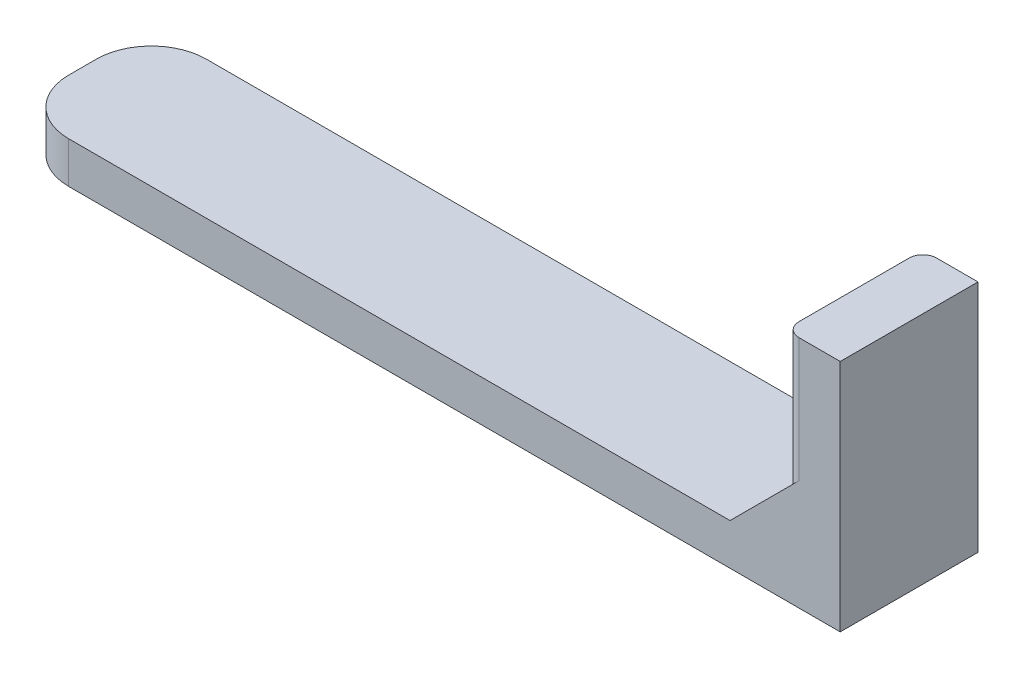
SolidWorks part; units mm, degrees
ref_plane "Plano frontal" through (0, 0, 0) normal (0, 0, 1) x (1, 0, 0)
ref_plane "Plano superior" through (0, 0, 0) normal (0, 1, 0) x (1, 0, 0)
ref_plane "Plano direito" through (0, 0, 0) normal (1, 0, 0) x (0, 0, -1)
sketch "Esboço1" plane through (0, 0, 0) normal (0, 1, 0) x (1, 0, 0)
  line L1 (-15, -2.5) -> (15, -2.5)
  line L2 (-15, -2.5) -> (-15, 2.5)
  line L3 (-15, 2.5) -> (15, 2.5)
  line L4 (15, -2.5) -> (15, 2.5)
  line L5 (-15, -2.5) -> (15, 2.5) construction
  line L6 (-15, 2.5) -> (15, -2.5) construction
  point P0 (0, 0)
  dimension "D1" = 30
  dimension "D2" = 5
extrude "Ressalto-extrusão1" add sketch "Esboço1" along normal blind 1.5
sketch "Esboço2" plane through (0, 1.5, 0) normal (0, 1, 0) x (1, 0, 0)
  line L0 (15, 2.5) -> (-15, 2.5) construction
  line L1 (15, -2.5) -> (13, -2.5)
  line L2 (15, -2.5) -> (15, 2.5)
  line L3 (15, 2.5) -> (13, 2.5)
  line L4 (13, -2.5) -> (13, 2.5)
  dimension "D1" = 2
extrude "Ressalto-extrusão2" add sketch "Esboço2" along normal blind 7
fillet "Filete1" radius 2 1 edges at (-15, 0.75, 2.5)
fillet "Filete2" radius 2 1 edges at (-15, 0.75, -2.5)
chamfer "Chanfro1" distance 2 angle 45 1 edges at (13, 1.5, 0)
fillet "Filete4" radius 0.5 1 edges at (13, 6, 2.5)
fillet "Filete5" radius 0.5 1 edges at (13, 6, -2.5)
